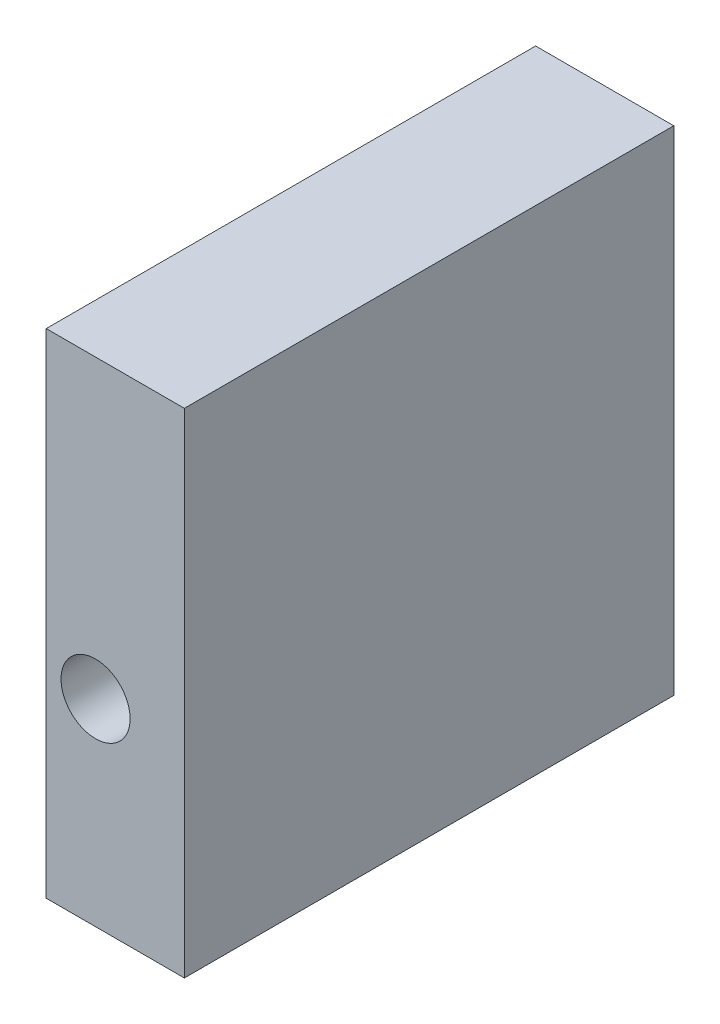
SolidWorks part; units mm, degrees
ref_plane "Front Plane" through (0, 0, 0) normal (0, 0, 1) x (1, 0, 0)
ref_plane "Top Plane" through (0, 0, 0) normal (0, 1, 0) x (1, 0, 0)
ref_plane "Right Plane" through (0, 0, 0) normal (1, 0, 0) x (0, 0, -1)
sketch "Sketch1" plane through (0, 0, 0) normal (0, 0, 1) x (1, 0, 0)
  line L0 (67, -55.1107) -> (11, -55.1107) construction
  line L1 (61.205, -55.1107) -> (68.205, -55.1107)
  line L2 (61.205, -55.1107) -> (61.205, -80.1107)
  line L3 (61.205, -80.1107) -> (68.205, -80.1107)
  line L4 (68.205, -55.1107) -> (68.205, -80.1107)
  dimension "D1" = 7
  dimension "D2" = 25
extrude "Boss-Extrude1" add sketch "Sketch1" along normal up to surface (24.8 mm away)
sketch "Sketch2" plane through (0, 0, 24.8) normal (0, 0, 1) x (1, 0, 0)
  line L0 (63.705, -55.1107) -> (63.705, -80.1107) construction
  line L1 (68.205, -55.1107) -> (61.205, -55.1107) construction
  line L2 (61.205, -80.1107) -> (68.205, -80.1107) construction
  line L3 (68.205, -80.1107) -> (68.205, -55.1107) construction
  circle A0 centre (63.705, -70.1107) radius 1.75
  circle A1 centre (63.705, -90.1107) radius 1.75
  dimension "D1" = 3.5
  dimension "D3" = 3.5
  dimension "D2" = 4.5
  dimension "D4" = 20
  dimension "D5" = 15
extrude "Cut-Extrude1" cut sketch "Sketch2" against normal through all
